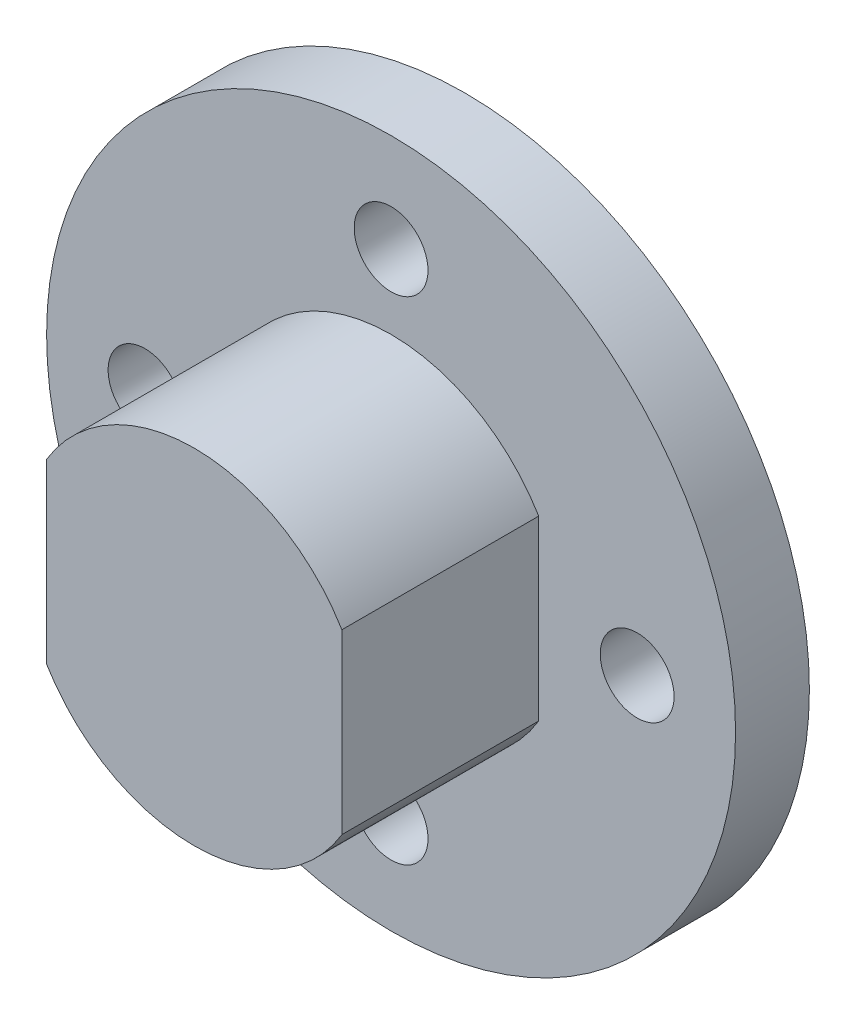
SolidWorks part; units mm, degrees
ref_plane "前视基准面" through (0, 0, 0) normal (0, 0, 1) x (1, 0, 0)
ref_plane "上视基准面" through (0, 0, 0) normal (0, 1, 0) x (1, 0, 0)
ref_plane "右视基准面" through (0, 0, 0) normal (1, 0, 0) x (0, 0, -1)
sketch "草图1" plane through (0, 0, 0) normal (0, 0, 1) x (1, 0, 0)
  circle A0 centre (0, 0) radius 14
  circle A3 centre (0, 10) radius 1.5
  circle A4 centre (10, 0) radius 1.5
  circle A5 centre (0, -10) radius 1.5
  circle A6 centre (-10, 0) radius 1.5
  point P15 (0, 0)
  point P18 (0, 3)
  point P21 (0, -3)
extrude "凸台-拉伸1" add sketch "草图1" along normal blind 3
sketch "草图3" plane through (0, 0, 3) normal (0, 0, 1) x (1, 0, 0)
  line L0 (6, 3.6056) -> (6, -3.6056)
  line L6 (-6, 3.6056) -> (-6, -3.6056)
  arc A2 (-6, 3.6056) -> (6, 3.6056) centre (0, 0) cw
  arc A3 (-6, -3.6056) -> (6, -3.6056) centre (0, 0) ccw
extrude "凸台-拉伸2" add sketch "草图3" along normal blind 8
